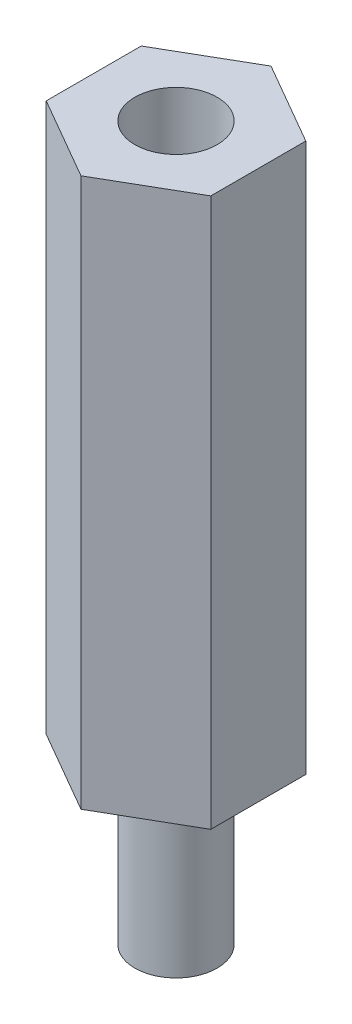
SolidWorks part; units mm, degrees
ref_plane "Płaszczyzna przednia" through (0, 0, 0) normal (0, 0, 1) x (1, 0, 0)
ref_plane "Płaszczyzna górna" through (0, 0, 0) normal (0, 1, 0) x (1, 0, 0)
ref_plane "Płaszczyzna prawa" through (0, 0, 0) normal (1, 0, 0) x (0, 0, -1)
sketch "Sketch1" plane through (0, 0, 0) normal (0, 1, 0) x (1, 0, 0)
  circle A0 centre (0, 0) radius 1.5
  dimension "D1" = 3
extrude "Boss-Extrude1" add sketch "Sketch1" along normal blind 6
sketch "Sketch2" plane through (0, 6, 0) normal (0, 1, 0) x (1, 0, 0)
  line L1 (-3, -1.7321) -> (0, -3.4641)
  line L2 (0, -3.4641) -> (3, -1.7321)
  line L3 (3, -1.7321) -> (3, 1.7321)
  line L4 (3, 1.7321) -> (0, 3.4641)
  line L5 (0, 3.4641) -> (-3, 1.7321)
  line L6 (-3, 1.7321) -> (-3, -1.7321)
  circle A0 centre (0, 0) radius 3 construction
  dimension "D1" = 6
extrude "Boss-Extrude2" add sketch "Sketch2" along normal blind 20
sketch "Sketch3" plane through (0, 26, 0) normal (0, 1, 0) x (1, 0, 0)
  circle A0 centre (0, 0) radius 1.5
  dimension "D1" = 3
extrude "Cut-Extrude1" cut sketch "Sketch3" against normal blind 6
